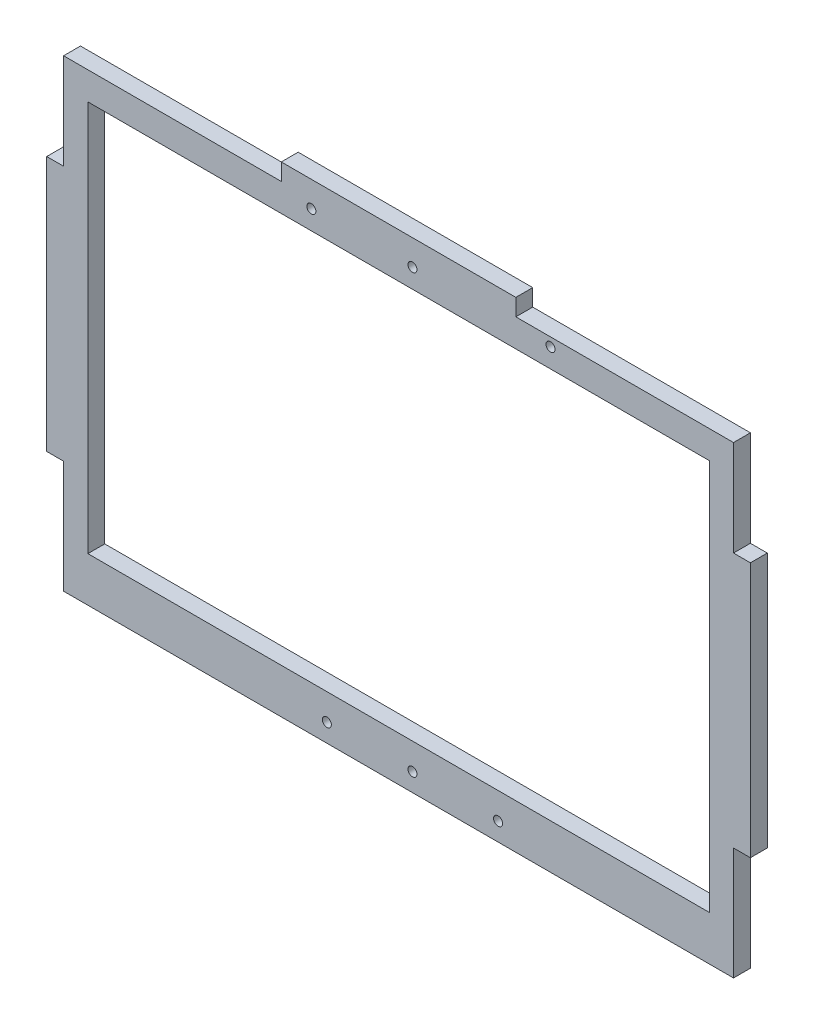
SolidWorks part; units mm, degrees
ref_plane "Front Plane" through (0, 0, 0) normal (0, 0, 1) x (1, 0, 0)
ref_plane "Top Plane" through (0, 0, 0) normal (0, 1, 0) x (1, 0, 0)
ref_plane "Right Plane" through (0, 0, 0) normal (1, 0, 0) x (0, 0, -1)
sketch "Sketch1" plane through (0, 0, 0) normal (0, 0, 1) x (1, 0, 0)
  line L1 (0, 0) -> (500, 0)
  line L2 (0, 0) -> (0, 341.5)
  line L3 (0, 341.5) -> (500, 341.5)
  line L4 (500, 0) -> (500, 341.5)
  dimension "D1" = 500
  dimension "D2" = 341.5
extrude "Boss-Extrude1" add sketch "Sketch1" along normal blind 12
sketch "Sketch3" plane through (0, 0, 12) normal (0, 0, 1) x (1, 0, 0)
  line L0 (0, 341.5) -> (0, 0) construction
  line L1 (29.24, 31.75) -> (470.76, 31.75)
  line L2 (29.24, 31.75) -> (29.24, 309.75)
  line L3 (29.24, 309.75) -> (470.76, 309.75)
  line L4 (470.76, 31.75) -> (470.76, 309.75)
  line L5 (500, 341.5) -> (0, 341.5) construction
  dimension "D1" = 441.52
  dimension "D2" = 278
  dimension "D3" = 29.24
  dimension "D4" = 31.75
sketch "Sketch5" plane through (0, 0, 12) normal (0, 0, 1) x (1, 0, 0)
  line L1 (0, 341.5) -> (12, 341.5)
  line L2 (0, 341.5) -> (0, 261.5)
  line L3 (0, 261.5) -> (12, 261.5)
  line L4 (12, 341.5) -> (12, 261.5)
  line L5 (0, 0) -> (12, 0)
  line L6 (0, 0) -> (0, 80)
  line L7 (0, 80) -> (12, 80)
  line L8 (12, 0) -> (12, 80)
  line L9 (500, 341.5) -> (488, 341.5)
  line L10 (500, 341.5) -> (500, 261.5)
  line L11 (500, 261.5) -> (488, 261.5)
  line L12 (488, 341.5) -> (488, 261.5)
  line L13 (500, 0) -> (488, 0)
  line L14 (500, 0) -> (500, 80)
  line L15 (500, 80) -> (488, 80)
  line L16 (488, 0) -> (488, 80)
  dimension "D1" = 12
  dimension "D2" = 80
extrude "Cut-Extrude2" cut sketch "Sketch5" against normal through all
extrude "Cut-Extrude3" cut sketch "Sketch3" against normal through all
sketch "Sketch6" plane through (0, 0, 12) normal (0, 0, 1) x (1, 0, 0)
  line L1 (488, 341.5) -> (333.3333, 341.5)
  line L2 (488, 341.5) -> (488, 329.5)
  line L3 (488, 329.5) -> (333.3333, 329.5)
  line L4 (333.3333, 341.5) -> (333.3333, 329.5)
  line L5 (12, 341.5) -> (166.6667, 341.5)
  line L6 (12, 341.5) -> (12, 329.5)
  line L7 (12, 329.5) -> (166.6667, 329.5)
  line L8 (166.6667, 341.5) -> (166.6667, 329.5)
  point P10 (333.3333, 335.5)
  dimension "D1" = 12
  dimension "D2" = 166.6667
extrude "Cut-Extrude4" cut sketch "Sketch6" against normal through all
scale "Scale1" scale about centroid uniform scaling yes scale factor 0.5
hole_wizard "M3 Clearance Slot1" positions "Sketch7" profile "Sketch8" size "M3" standard "ANSI Metric" slot yes end condition through all
sketch "Sketch7" plane through (0, 0, 9) normal (0, 0, 1) x (1, 0, 0)
  line L0 (139.62, 232.6917) -> (139.62, 93.6917) construction
  line L1 (360.38, 232.6917) -> (139.62, 232.6917) construction
  line L2 (139.62, 93.6917) -> (360.38, 93.6917) construction
  point P0 (219.02, 239.4917)
  point P2 (303.98, 239.4917)
  point P4 (224.52, 84.2917)
  point P6 (285.36, 84.2917)
  dimension "D1" = 79.4
  dimension "D2" = 6.8
  dimension "D3" = 6.8
  dimension "D4" = 164.36
  dimension "D5" = 84.9
  dimension "D6" = 9.4
  dimension "D7" = 9.4
  dimension "D8" = 145.74
sketch "Sketch8" plane through (219.02, 239.4917, 9) normal (1, 0, 0) x (0, -1, 0)
  line L0 (0, 0) -> (0, 6)
  line L1 (0, 6) -> (1.6, 6)
  line L2 (1.6, 6) -> (1.6, 0)
  line L5 (1.6, 0) -> (0, 0)
  line L11 (0, -6.35) -> (0, 107.95) construction
  dimension "Thru Hole Dia." = 3.2
  dimension "Thru Hole Depth" = 6
hole_wizard "M3 Clearance Slot2" positions "Sketch9" profile "Sketch10" size "M3" standard "ANSI Metric" slot yes end condition through all
sketch "Sketch9" plane through (0, 0, 9) normal (0, 0, 1) x (1, 0, 0)
  line L0 (131, 77.8167) -> (369, 77.8167) construction
  line L1 (360.38, 232.6917) -> (139.62, 232.6917) construction
  circle A0 centre (224.52, 84.2917) radius 1.6 construction
  circle A1 centre (285.36, 84.2917) radius 1.6 construction
  circle A2 centre (219.02, 239.4917) radius 1.6 construction
  point P0 (254.94, 84.2967)
  point P9 (254.94, 239.4917)
  dimension "D2" = 30.42
  dimension "D4" = 35.92
  dimension "D1" = 6.48
  dimension "D3" = 30.42
  dimension "D5" = 6.8
sketch "Sketch10" plane through (254.94, 84.2967, 9) normal (1, 0, 0) x (0, -1, 0)
  line L0 (0, 0) -> (0, 6)
  line L1 (0, 6) -> (1.6, 6)
  line L2 (1.6, 6) -> (1.6, 0)
  line L5 (1.6, 0) -> (0, 0)
  line L11 (0, -6.35) -> (0, 107.95) construction
  dimension "Thru Hole Dia." = 3.2
  dimension "Thru Hole Depth" = 6
